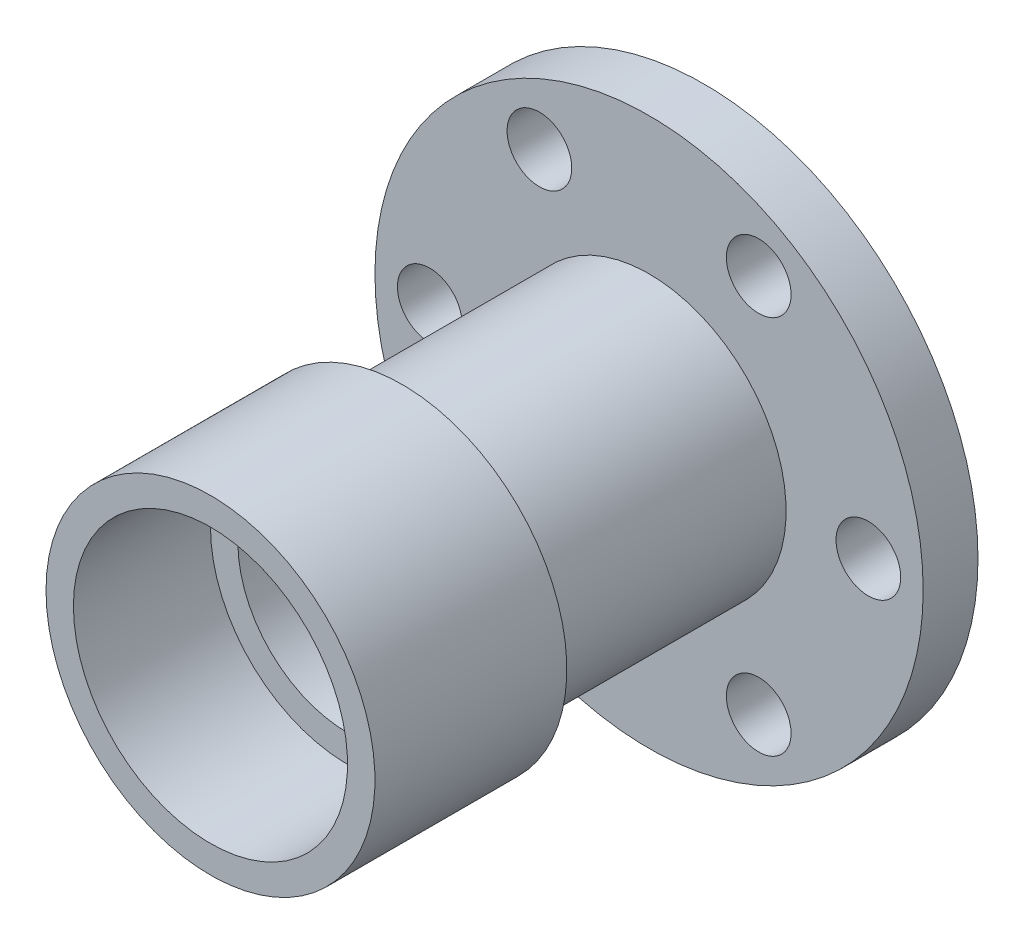
SolidWorks part; units mm, degrees
ref_plane "Front Plane" through (0, 0, 0) normal (0, 0, 1) x (1, 0, 0)
ref_plane "Top Plane" through (0, 0, 0) normal (0, 1, 0) x (1, 0, 0)
ref_plane "Right Plane" through (0, 0, 0) normal (1, 0, 0) x (0, 0, -1)
sketch "Sketch1" plane through (0, 0, 0) normal (1, 0, 0) x (0, 0, -1)
  line L0 (0, 0) -> (-90, 0) construction
  line L1 (0, 20) -> (0, 50)
  line L2 (0, 50) -> (-10, 50)
  line L3 (-10, 50) -> (-10, 25)
  line L4 (-10, 25) -> (-55, 25)
  line L5 (-55, 25) -> (-55, 30)
  line L6 (-55, 30) -> (-90, 30)
  line L7 (-90, 30) -> (-90, 25)
  line L8 (-90, 25) -> (-65, 25)
  line L9 (-65, 25) -> (-65, 20)
  line L10 (-65, 20) -> (0, 20)
  point P3 (0, 21.9811)
  point P13 (0, 0)
  point P14 (0, 0)
  dimension "D1" = 90
  dimension "D2" = 40
  dimension "D3" = 50
  dimension "D4" = 60
  dimension "D5" = 50
  dimension "D6" = 65
  dimension "D7" = 10
  dimension "D8" = 100
  dimension "D9" = 35
revolve "Revolve1" add sketch "Sketch1" angle 360 about L0
sketch "Sketch2" plane through (0, 0, 10) normal (0, 0, 1) x (1, 0, 0)
  circle A0 centre (0, 0) radius 40 construction
  circle A1 centre (40, 0) radius 5.9
  circle A2 centre (20, -34.641) radius 5.9
  circle A3 centre (-20, -34.641) radius 5.9
  circle A4 centre (-40, 0) radius 5.9
  circle A5 centre (-20, 34.641) radius 5.9
  circle A6 centre (20, 34.641) radius 5.9
  point P6 (0, 0)
  point P7 (0, 0)
  point P17 (0, 0)
  dimension "D1" = 80
  dimension "D2" = 11.8
  dimension "D3" = 6
extrude "Cut-Extrude1" cut sketch "Sketch2" against normal up to surface (10 mm away) up to face at (-50, 0, 0)
